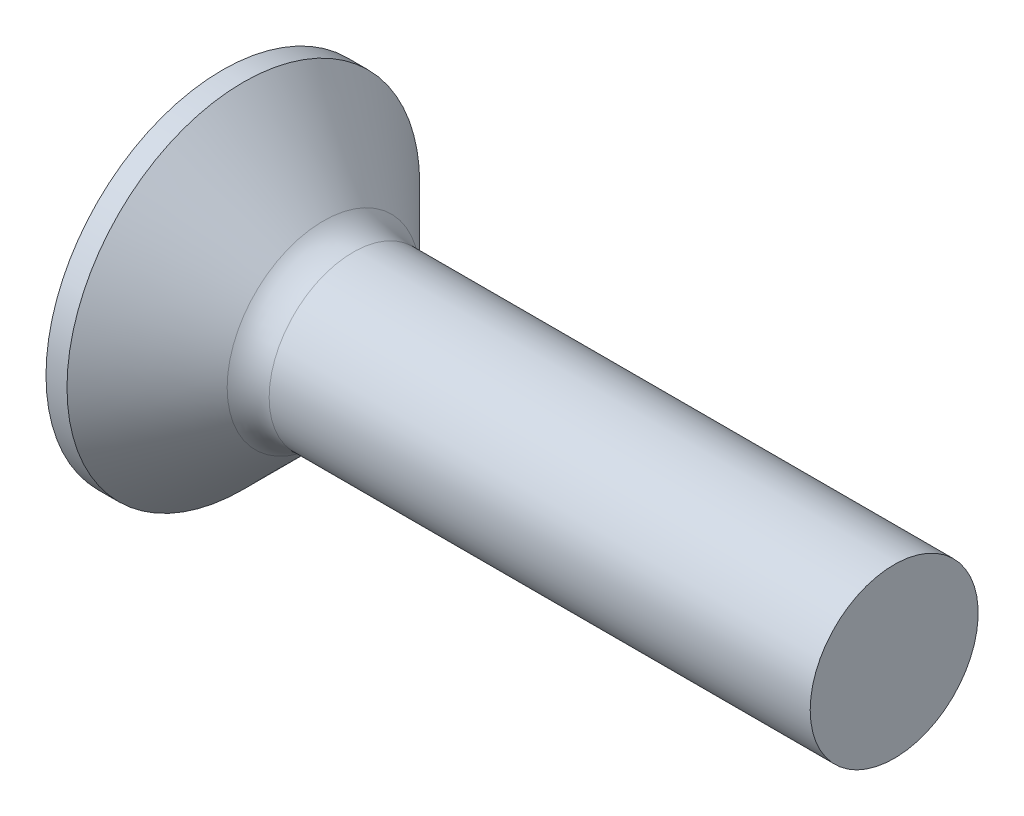
SolidWorks part; units mm, degrees
revolve "Base-Revolve" add sketch "BodySke" angle 360 about L5
sketch "BodySke" plane through (0, 0, 0) normal (0, 0, 1) x (1, 0, 0)
  line L0 (0, 0) -> (0, 4.2)
  line L1 (0, 4.2) -> (0.5, 4.2)
  line L2 (2.7, 2) -> (16, 2)
  line L3 (16, 2) -> (16, 0)
  line L4 (16, 0) -> (0, 0)
  line L5 (-6.35, 0) -> (82.55, 0) construction
  line L6 (2.7, -2) -> (16, -2) construction
  line L7 (0.5, -4.2) -> (2.7, -2) construction
  line L8 (0.5, 4.2) -> (2.7, 2)
  line L9 (0, -4.2) -> (0.5, -4.2) construction
  line L10 (3.4, 3.5875) -> (3.4, -5.9375) construction
  line L11 (0, 6.35) -> (0, -3.175) construction
  dimension "Head_ang" = 90
cosmetic thread "ThreadCosmetic" [suppressed] parameters "Thread_length"=8.4, "Thread_minor"=3.22
ref_plane "Plane1" through (0, 0, 0) normal (0, 0, 1) x (1, 0, 0)
ref_plane "Plane2" through (0, 0, 0) normal (0, 1, 0) x (1, 0, 0)
ref_plane "Plane3" through (0, 0, 0) normal (1, 0, 0) x (0, 0, -1)
other "Configuration Table"
fillet "Fillet1" radius 1 1 edges at (2.7, 0, 2)
sketch "Sketch3" plane through (0, 0, 0) normal (-1, 0, 0) x (0, 0, 1)
  line L0 (-0.515, 2.2) -> (0.515, 2.2)
  line L1 (0.515, 2.2) -> (0.515, -2.2)
  line L2 (0.515, -2.2) -> (-0.515, -2.2)
  line L3 (-0.515, -2.2) -> (-0.515, 2.2)
  dimension "D1" = 0.95
  dimension "D2" = 0.24
ref_plane "Plane4" through (2.51, 0, 0) normal (-1, 0, 0) x (0, 0, 1)
sketch "Sketch4" plane through (2.51, 0, 0) normal (-1, 0, 0) x (0, 0, 1)
  line L0 (-0.515, 0.9486) -> (0.515, 0.9486)
  line L3 (0.515, 0.9486) -> (0.515, -0.9486)
  line L4 (0.515, -0.9486) -> (-0.515, -0.9486)
  line L5 (-0.515, -0.9486) -> (-0.515, 0.9486)
  dimension "D2" = 0.7034
  dimension "D1" = 0.48
  dimension "D4" = 0.3517
  dimension "D3" = 0.24
loft "Recess" cut profiles "Sketch3", "Sketch4"
pattern_circular "RecPat" count 2 every 90 about axis through (0, 0, 0) along (1, 0, 0) of "Recess"
sketch "RecCorSke" plane through (0, 0, 0) normal (0, 0, 1) x (1, 0, 0)
  line L0 (-3.175, 0) -> (15.875, 0) construction
  line L2 (0, 0) -> (0, 1.0265)
  line L3 (0, 1.0265) -> (2.51, 0.851)
  line L4 (2.51, 0.851) -> (2.7865, 0)
  line L5 (2.7865, 0) -> (0, 0)
  dimension "Depth" = 1.2
  dimension "Draft_angle" = 4
  dimension "Bottom_angle" = 18
revolve "RecessCore" cut sketch "RecCorSke" angle 360 about L0
sketch "ThdSchSke" plane through (0, 0, 0) normal (0, 0, 1) x (1, 0, 0)
  line L0 (3.4, -1.61) -> (3.1269, -2)
  line L1 (3.4, -1.61) -> (3.6731, -2)
  line L2 (3.6731, -2) -> (3.6731, -2.5)
  line L3 (-3.175, 0) -> (5.1513, 0) construction
  line L5 (3.6731, -2.5) -> (3.1269, -2.5)
  line L6 (3.1269, -2.5) -> (3.1269, -2)
  line L7 (0, 4.2) -> (0, -4.2) construction
  dimension "Thread_minor" = 1.548
  dimension "Diameter" = 2
  dimension "Start" = 1.6
revolve "ThreadSchematic" [suppressed] cut sketch "ThdSchSke" angle 360 about L3
pattern_linear "ThdSchPat" [suppressed]
equation "\"D1@Sketch3\" = \"Cross_dia@Sketch3\" / 2"
equation "\"D2@Sketch3\" = \"Cross_width@Sketch3\" / 2"
equation "\"Depth@RecCorSke\" = \"Cross_depth@Plane4\""
equation "\"D1@Sketch4\" = \"Cross_width@Sketch3\""
equation "\"D2@Sketch4\" = \"Cross_dia@Sketch3\" - 2.0 * \"Cross_depth@Plane4\" * tan(26.5  * 0.017453292)"
equation "\"D3@Sketch4\" = \"D1@Sketch4\" / 2"
equation "\"D4@Sketch4\" = \"D2@Sketch4\" / 2"
equation "\"Thread_length@ThreadCosmetic\" = ((sgn( (\"Length@BodySke\" - \"Advance@BodySke\" * 1.0 - \"Head_ht@BodySke\" ) - \"Thread_nom@BodySke\" )-1)*( (\"Length@BodySke\" - \"Advance@BodySke\" * 1.0 - \"Head_ht@BodySke\" ) - \"Thread_nom@BodySke\" ))/-2+ \"Thread_nom@BodySke\""
equation "\"Thread_minor@ThdSchSke\" = \"Thread_minor@ThreadCosmetic\""
equation "\"Diameter@ThdSchSke\" = \"Diameter@BodySke\""
equation "\"Overcut@ThdSchSke\" = \"Diameter@BodySke\" * 1.25"
equation "\"Start@ThdSchSke\" = 0.000001 + \"Length@BodySke\" - \"Thread_length@ThreadCosmetic\"  '---Countersunk---"
equation "\"Num_threads@ThdSchPat\" = int( \"Thread_length@ThreadCosmetic\" / \"Advance@BodySke\" + 0.999 )  + 1"
equation "\"Advance@ThdSchPat\" = \"Thread_length@ThreadCosmetic\" /  (\"Num_threads@ThdSchPat\" - 1) 'relax it"
